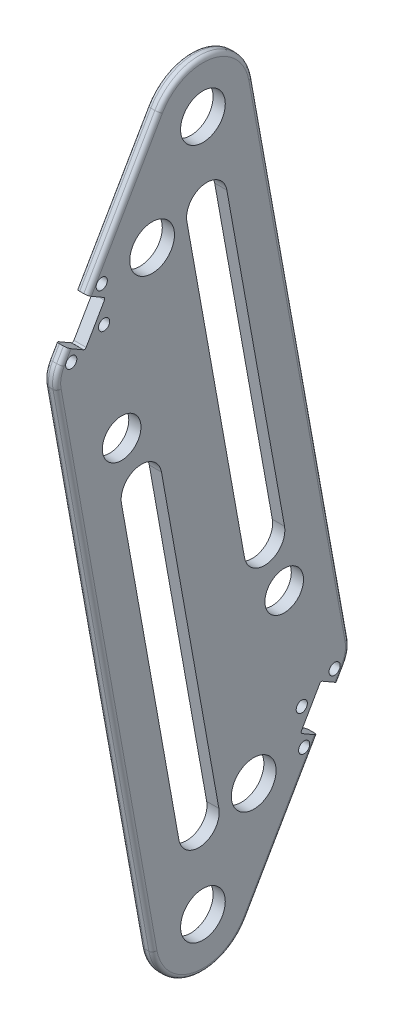
SolidWorks part; units mm, degrees
ref_plane "前视基准面" through (0, 0, 0) normal (0, 0, 1) x (1, 0, 0)
ref_plane "上视基准面" through (0, 0, 0) normal (0, 1, 0) x (1, 0, 0)
ref_plane "右视基准面" through (0, 0, 0) normal (1, 0, 0) x (0, 0, -1)
other "Configuration Table"
sketch "草图1" plane through (0, 0, 0) normal (1, 0, 0) x (0, 0, -1)
  line L0 (0, 0) -> (40, -222)
  line L1 (40, -222) -> (-25, -43.3013)
  line L2 (-25, -43.3013) -> (0, 0)
  line L3 (0, 0) -> (0, -340) construction
  line L4 (0, -340) -> (25, -296.6987)
  line L5 (25, -296.6987) -> (-40, -117)
  line L6 (-40, -117) -> (0, -340)
  line L8 (0, -340) -> (-40, -340)
  line L11 (-40, -340) -> (-40, -117)
  circle A0 centre (0, 0) radius 11
  circle A1 centre (-25, -43.3013) radius 11
  circle A2 centre (25, -296.6987) radius 11
  circle A3 centre (0, -340) radius 11
  circle A4 centre (40, -222) radius 9.5
  circle A5 centre (-40, -117) radius 9.5
  circle A6 centre (-25, -43.3013) radius 14
  circle A7 centre (-40, -117) radius 11.5
  dimension "D7" = 22
  dimension "D8" = 19
  dimension "D9" = 28
  dimension "D10" = 23
  dimension "D1" = 50
  dimension "D2" = 40
  dimension "D3" = 222
  dimension "D4" = 40
  dimension "D5" = 340
  dimension "D6" = 223
  dimension "D11" = 30
  dimension "D12" = 30
sketch "草图2" plane through (0, 0, 0) normal (1, 0, 0) x (0, 0, -1)
  line L0 (12.4943, 71.6408) -> (-72.7516, -76.0094)
  line L1 (-25, -43.3013) -> (0, 0) construction
  line L2 (-72.7516, -76.0094) -> (-12.5358, -411.7126)
  line L3 (-12.5358, -411.7126) -> (72.9169, -263.7043)
  line L4 (72.9169, -263.7043) -> (12.4943, 71.6408)
  line L5 (-40, -117) -> (0, -340) construction
  line L6 (0, 0) -> (40, -222) construction
  line L7 (0, -340) -> (25, -296.6987) construction
  circle A0 centre (-40, -117) radius 9.5 construction
  circle A1 centre (25, -296.6987) radius 11 construction
  circle A2 centre (0, -340) radius 11 construction
  circle A3 centre (-25, -43.3013) radius 11 construction
  circle A4 centre (40, -222) radius 9.5 construction
  circle A5 centre (0, 0) radius 11 construction
  circle A6 centre (-40, -117) radius 9.5
  circle A7 centre (25, -296.6987) radius 11
  circle A8 centre (0, -340) radius 11
  circle A9 centre (-25, -43.3013) radius 11
  circle A10 centre (40, -222) radius 9.5
  circle A11 centre (0, 0) radius 11
  dimension "D1" = 25
  dimension "D2" = 25
  dimension "D3" = 25
  dimension "D4" = 25
extrude "凸台-拉伸1" add sketch "草图2" along normal blind 6
sketch "草图3" plane through (6, 0, 0) normal (1, 0, 0) x (0, 0, -1)
  line L1 (12.4943, 71.6408) -> (-72.7516, -76.0094) construction
  line L3 (-72.7516, -76.0094) -> (-12.5358, -411.7126) construction
  line L5 (72.9169, -263.7043) -> (12.4943, 71.6408) construction
  line L8 (-12.5358, -411.7126) -> (72.9169, -263.7043) construction
  line L12 (-30.2487, -143.0438) -> (-2, -300.5304) construction
  line L13 (-20.4058, -141.2783) -> (7.843, -298.7648)
  line L14 (-40.0916, -144.8094) -> (-11.8429, -302.2959)
  line L15 (-40, -117) -> (0, -340) construction
  line L16 (-16.1243, -221.7871) -> (-20, -228.5) construction
  line L17 (0, 0) -> (40, -222) construction
  line L18 (1.9419, -38.9745) -> (30.3139, -196.4389) construction
  line L19 (11.7834, -37.2012) -> (40.1554, -194.6656)
  line L20 (-7.8996, -40.7477) -> (20.4724, -198.2121)
  line L21 (16.1279, -117.7067) -> (20, -111) construction
  arc A4 (-20.4058, -141.2783) -> (-40.0916, -144.8094) centre (-30.2487, -143.0438) ccw
  arc A5 (-11.8429, -302.2959) -> (7.843, -298.7648) centre (-2, -300.5304) ccw
  arc A6 (11.7834, -37.2012) -> (-7.8996, -40.7477) centre (1.9419, -38.9745) ccw
  arc A7 (20.4724, -198.2121) -> (40.1554, -194.6656) centre (30.3139, -196.4389) ccw
  point P30 (-16.1243, -221.7871)
  point P47 (16.1279, -117.7067)
  dimension "D7" = 10
  dimension "D9" = 10
  dimension "D5" = 160
  dimension "D6" = 30
  dimension "D8" = 160
  dimension "D10" = 30
extrude "切除-拉伸1" cut sketch "草图3" against normal blind 10
fillet "圆角1" radius 25 2 edges at (3, -411.7126, 12.5358) (3, 71.6408, -12.4943)
sketch "草图4" plane through (6, 0, 0) normal (1, 0, 0) x (0, 0, -1)
  line L0 (-66.6506, -65.4423) -> (-56.6506, -48.1218)
  line L1 (-66.6506, -65.4423) -> (-57.9904, -70.4423)
  line L2 (-56.6506, -48.1218) -> (-47.9904, -53.1218)
  line L3 (-57.9904, -70.4423) -> (-47.9904, -53.1218)
  line L4 (-21.6506, 12.5) -> (-72.7516, -76.0094) construction
  line L5 (-61.6506, -56.782) -> (-48.6603, -64.282) construction
  line L6 (-49.8205, -46.2917) -> (-64.8205, -72.2724) construction
  line L7 (-61.6506, -56.782) -> (-52.9904, -61.782) construction
  line L8 (61.6506, -283.218) -> (52.9904, -278.218) construction
  line L9 (21.6506, -352.5) -> (72.9169, -263.7043) construction
  line L10 (64.8205, -267.7276) -> (49.8205, -293.7083) construction
  line L11 (61.6506, -283.218) -> (48.6603, -275.718) construction
  line L12 (47.9904, -286.8782) -> (57.9904, -269.5577)
  line L13 (66.6506, -274.5577) -> (57.9904, -269.5577)
  line L14 (56.6506, -291.8782) -> (47.9904, -286.8782)
  line L15 (56.6506, -291.8782) -> (66.6506, -274.5577)
  line L16 (-61.6506, -56.782) -> (-52.9904, -61.782) construction
  circle A0 centre (-25, -43.3013) radius 20 construction
  circle A1 centre (-49.8205, -46.2917) radius 2.75
  circle A2 centre (-64.8205, -72.2724) radius 2.75
  circle A3 centre (-48.6603, -64.282) radius 2.75
  circle A4 centre (25, -296.6987) radius 20 construction
  circle A5 centre (48.6603, -275.718) radius 2.75
  circle A6 centre (49.8205, -293.7083) radius 2.75
  circle A7 centre (64.8205, -267.7276) radius 2.75
  point P16 (-57.3205, -59.282)
  point P37 (57.3205, -280.718)
  dimension "D3" = 40
  dimension "D6" = 5.5
  dimension "D7" = 20
  dimension "D11" = 5.5
  dimension "D1" = 20
  dimension "D2" = 10
  dimension "D4" = 15
  dimension "D5" = 30
  dimension "D8" = 10
  dimension "D9" = 30
  dimension "D10" = 15
extrude "切除-拉伸2" cut sketch "草图4" against normal blind 10
fillet "圆角2" radius 15 2 edges at (3, -76.0094, 72.7516) (3, -263.7043, -72.9169)
fillet "圆角3" radius 1 4 edges at (3, -70.4423, 57.9904) (3, -53.1218, 47.9904) (3, -286.8782, -47.9904) (3, -269.5577, -57.9904)
sketch "草图5" plane through (6, 0, 0) normal (1, 0, 0) x (0, 0, -1)
  line L0 (0, 0) -> (0, -340) construction
fillet "圆角4" radius 2 20 edges at (6, -68.3509, 68.3299) (6, -76.1767, 71.7948) (6, -212.9109, 48.1953) (6, -364.6266, 4.3049) (0, -68.3509, 68.3299) (0, -76.1767, 71.7948) (0, -212.9109, 48.1953) (0, -364.6266, 4.3049) (0, -271.5088, -68.4109) (0, -263.537, -71.9578) (0, -17.8109, 39.1506) (0, 24.6283, -4.2952) (6, -271.5088, -68.4109) (6, -263.537, -71.9578) (6, -17.8109, 39.1506) (6, 24.6283, -4.2952) (6, -322.1891, -39.1506) (0, -322.1891, -39.1506) (0, -126.9335, -48.2735) (6, -126.9335, -48.2735)
ref_plane "基准面1" through (0, 0, 0) normal (0, 0, 1) x (0, -1, 0)
